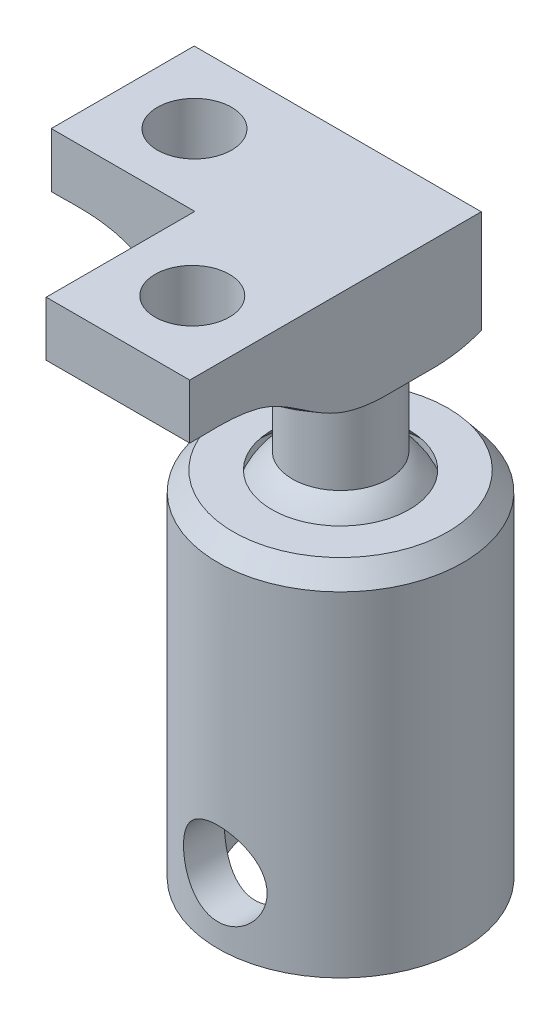
SolidWorks part; units mm, degrees
ref_plane "Alzado" through (0, 0, 0) normal (0, 0, 1) x (1, 0, 0)
ref_plane "Planta" through (0, 0, 0) normal (0, 1, 0) x (1, 0, 0)
ref_plane "Vista lateral" through (0, 0, 0) normal (1, 0, 0) x (0, 0, -1)
sketch "Croquis2" plane through (0, 0, 0) normal (0, 0, 1) x (1, 0, 0)
  line L0 (4.6, 0) -> (6.6, 0)
  line L5 (6.6, 0) -> (6.6, 18)
  line L7 (4.6, 18.0674) -> (4.6, 14.1)
  line L8 (4.6, 18.0674) -> (3.7, 19.0219)
  line L11 (0, 12.4272) -> (0, 20.8)
  line L12 (5.7773, 19.0219) -> (6.6, 18)
  line L13 (3.7, 19.0219) -> (5.7773, 19.0219)
  line L22 (4.6, 11.5) -> (4.6, 0)
  line L23 (0.4773, 12.4272) -> (0, 12.4272)
  arc A0 (0.4773, 12.4272) -> (0, 20.8) centre (0, 16.6) ccw
  arc A1 (4.6, 14.1) -> (4.6, 11.5) centre (4.6, 12.8) ccw
  dimension "D6" = 11.5
  dimension "D7" = 16.6
  dimension "D1" = 2
  dimension "D2" = 18
  dimension "D3" = 4.6
  dimension ".88" = 0.9
revolve "Revolución2" add sketch "Croquis2" angle 360 about L11
ref_plane "Plano1" through (0, 0, 7) normal (0, 0, 1) x (1, 0, 0)
sketch "Croquis3" plane through (0, 0, 7) normal (0, 0, 1) x (1, 0, 0)
  circle A0 centre (0, 6) radius 2
ref_plane "Plano2" through (0, 0, -8) normal (0, 0, 1) x (1, 0, 0)
ref_plane "Plano3" through (0, 23, 0) normal (0, 1, 0) x (1, 0, 0)
sketch "Croquis5" plane through (0, 23, 0) normal (0, 1, 0) x (1, 0, 0)
  circle A0 centre (0, 0) radius 2.6
extrude "Saliente-Extruir1" add sketch "Croquis5" along normal blind 2 and the other way blind 4 contours A0
sketch "Croquis6" plane through (0, 25, 0) normal (0, 1, 0) x (1, 0, 0)
  line L2 (-3.7277, -3.8476) -> (3.7277, -3.8476)
  line L3 (-3.7277, -3.8476) -> (-3.7277, 3.8476)
  line L4 (-3.7277, 3.8476) -> (3.7277, 3.8476)
  line L5 (3.7277, -3.8476) -> (3.7277, 3.8476)
  line L6 (-3.7277, -3.8476) -> (3.7277, 3.8476) construction
  line L7 (-3.7277, 3.8476) -> (3.7277, -3.8476) construction
  point P1 (0, 0)
extrude "Saliente-Extruir2" add sketch "Croquis6" along normal blind 6
sketch "Croquis14" plane through (-3.7277, 0, 0) normal (-1, 0, 0) x (0, 0, 1)
  line L1 (-3.8476, 31) -> (3.8476, 31)
  line L2 (-3.8476, 31) -> (-3.8476, 25)
  line L3 (-3.8476, 25) -> (3.8476, 25)
  line L4 (3.8476, 31) -> (3.8476, 25)
extrude "Saliente-Extruir4" add sketch "Croquis14" along normal blind 8
sketch "Croquis15" plane through (0, 0, 3.8476) normal (0, 0, 1) x (1, 0, 0)
  line L0 (-11.7277, 25) -> (3.7277, 25) construction
  line L1 (3.7277, 31) -> (-4, 31)
  line L2 (3.7277, 31) -> (3.7277, 25)
  line L3 (3.7277, 25) -> (-4, 25)
  line L4 (-4, 31) -> (-4, 25)
extrude "Saliente-Extruir5" add sketch "Croquis15" along normal blind 8
sketch "Croquis18" plane through (0, 0, 0) normal (0, 0, 1) x (1, 0, 0)
  line L3 (3.7277, 25) -> (-11.7277, 25) construction
  line L4 (-2.6, 25) -> (2.6, 25) construction
  line L5 (0, 25) -> (0, 26.4385)
  line L7 (-11.7277, 31) -> (-11.7277, 25) construction
  line L9 (-11.7277, 28.0592) -> (-12.8647, 28.0592)
  line L10 (-12.8647, 28.0592) -> (-12.8647, 21.8345)
  line L11 (-12.8647, 21.8345) -> (-4, 21.9676)
  line L12 (-4, 21.9676) -> (-4, 25)
  spline S0 degree 3 poles (-4, 25) (-5.8326, 25.2268) (-7.6075, 28.057) (-10.6871, 28.0956) (-11.7277, 28.0592) knots 0 0 0 0 0.623195 1 1 1 1
revolve "Cortar-Revolución10" cut sketch "Croquis18" angle 360 about L5
sketch "Croquis19" plane through (0, 31, 0) normal (0, 1, 0) x (1, 0, 0)
  circle A0 centre (-7.8638, 0) radius 2
  circle A1 centre (-0.1362, -7.8476) radius 2
extrude "Cortar-Extruir3" cut sketch "Croquis19" against normal up to next
sketch "Croquis4" plane through (0, 0, -8) normal (0, 0, 1) x (1, 0, 0)
  circle A0 centre (0, 3.5) radius 2.25
  dimension "D1" = 3.5
  dimension "D2" = 4.5
extrude "Cortar-Extruir2" cut sketch "Croquis4" along normal blind 23
sketch "Croquis20" plane through (0, 31, 0) normal (0, 1, 0) x (1, 0, 0)
  line L0 (-7.8638, 0) -> (-7.8638, 3.8476)
  line L1 (3.7277, 3.8476) -> (-11.7277, 3.8476) construction
  line L2 (-7.8638, 3.8476) -> (3.7277, 3.8476)
  line L3 (-0.1362, -7.8476) -> (3.7277, -7.8476)
  line L4 (3.7277, -11.8476) -> (3.7277, 3.8476) construction
